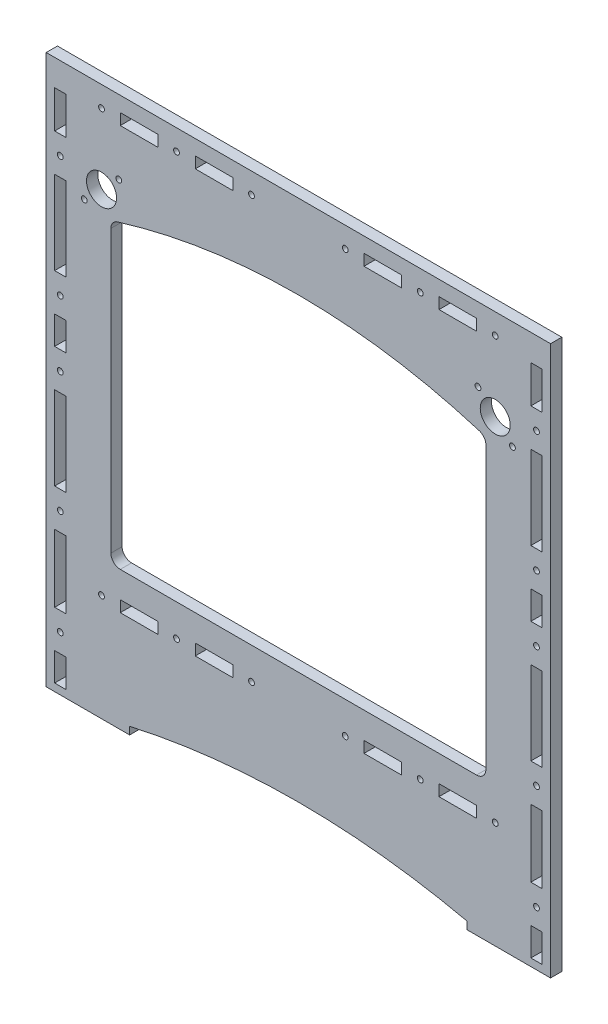
SolidWorks part; units mm, degrees
ref_plane "Front Plane" through (0, 0, 0) normal (0, 0, 1) x (1, 0, 0)
ref_plane "Top Plane" through (0, 0, 0) normal (0, 1, 0) x (1, 0, 0)
ref_plane "Right Plane" through (0, 0, 0) normal (1, 0, 0) x (0, 0, -1)
sketch "Sketch1" plane through (0, 0, 0) normal (0, 0, 1) x (1, 0, 0)
  line L1 (0, 0) -> (260, 0)
  line L2 (0, 0) -> (0, 270)
  line L3 (0, 270) -> (260, 270)
  line L4 (260, 0) -> (260, 270)
  dimension "D1" = 270
  dimension "D2" = 260
extrude "Boss-Extrude1" add sketch "Sketch1" along normal blind 6
sketch "Sketch2" plane through (0, 0, 0) normal (0, 0, -1) x (-1, 0, 0)
  line L0 (-130, 270) -> (-130, 0) construction
  line L1 (-225, 56) -> (-205, 56)
  line L2 (-225, 56) -> (-225, 50)
  line L3 (-225, 50) -> (-205, 50)
  line L4 (-205, 56) -> (-205, 50)
  line L5 (-185, 56) -> (-165, 56)
  line L6 (-185, 56) -> (-185, 50)
  line L7 (-185, 50) -> (-165, 50)
  line L8 (-165, 56) -> (-165, 50)
  line L9 (-260, 270) -> (0, 270) construction
  line L10 (0, 0) -> (-260, 0) construction
  line L11 (-260, 0) -> (-260, 270) construction
  line L12 (-225, 53) -> (-165, 53) construction
  line L13 (-130, 0) -> (-130, -73.8705) construction
  line L14 (-130, -73.8705) -> (-130, -196.098) construction
  line L16 (-220, 0) -> (-40, 0)
  line L17 (-75, 50) -> (-95, 50)
  line L18 (-95, 56) -> (-95, 50)
  line L19 (-75, 56) -> (-95, 56)
  line L20 (-75, 56) -> (-75, 50)
  line L21 (-35, 50) -> (-55, 50)
  line L22 (-55, 56) -> (-55, 50)
  line L23 (-35, 56) -> (-55, 56)
  line L24 (-35, 56) -> (-35, 50)
  arc A0 (-220, 0) -> (-40, 0) centre (-130, -400) cw
  point P23 (-130, 10)
  point P26 (-130, 10)
  dimension "D9" = 40
  dimension "D1" = 35
  dimension "D2" = 20
  dimension "D3" = 20
  dimension "D4" = 20
  dimension "D5" = 6
  dimension "D6" = 6
  dimension "D7" = 50
  dimension "D8" = 3
  dimension "D12" = 10
extrude "Cut-Extrude1" cut sketch "Sketch2" against normal blind 6
sketch "Sketch3" plane through (0, 0, 0) normal (0, 0, -1) x (-1, 0, 0)
  line L0 (-260, 0) -> (-260, 270) construction
  line L1 (-225, 70) -> (-35, 70)
  line L2 (-230, 75) -> (-230, 220)
  line L4 (-30, 75) -> (-30, 220)
  line L5 (0, 270) -> (0, 0) construction
  line L6 (-220, 0) -> (-260, 0) construction
  line L7 (-260, 270) -> (0, 270) construction
  line L16 (-35, 225) -> (-225, 225)
  arc A0 (-35, 70) -> (-30, 75) centre (-35, 75) ccw
  arc A1 (-225, 70) -> (-230, 75) centre (-225, 75) cw
  arc A2 (-230, 220) -> (-225, 225) centre (-225, 220) cw
  arc A3 (-35, 225) -> (-30, 220) centre (-35, 220) cw
  dimension "D5" = 5
  dimension "D6" = 45
  dimension "D4" = 5
  dimension "D1" = 30
  dimension "D2" = 30
  dimension "D3" = 70
extrude "Cut-Extrude2" cut sketch "Sketch3" against normal blind 10 contours L4 A3 L16 A2 L2 A1 L1 A0
sketch "Sketch4" plane through (0, 0, 0) normal (0, 0, -1) x (-1, 0, 0)
  line L1 (-260, 270) -> (-254, 270)
  line L2 (-260, 270) -> (-260, 264)
  line L5 (-220, 0) -> (-260, 0) construction
  line L6 (-260, 270) -> (-254, 270)
  line L7 (-260, 270) -> (-260, 255)
  line L8 (-260, 0) -> (-254, 0)
  line L9 (-254, 264) -> (-254, 255)
  line L11 (-254, 15) -> (-260, 15)
  line L13 (-254, 35) -> (-260, 35)
  line L15 (-254, 71) -> (-260, 71)
  line L17 (-254, 91) -> (-260, 91)
  line L19 (-260, 135.5) -> (-254, 135.5)
  line L21 (-260, 155.5) -> (-254, 155.5)
  line L23 (-254, 170.5) -> (-260, 170.5)
  line L25 (-254, 190.5) -> (-260, 190.5)
  line L27 (-254, 235) -> (-260, 235)
  line L29 (-254, 255) -> (-260, 255)
  line L33 (-254, 264) -> (-254, 270)
  line L36 (-205, 56) -> (-225, 56) construction
  line L38 (-130, 270) -> (-130, 0) construction
  line L39 (-260, 270) -> (0, 270) construction
  line L40 (-260, 15) -> (-260, 0)
  line L41 (-260, 270) -> (-254, 270)
  line L42 (-260, 270) -> (-260, 255)
  line L43 (-260, 255) -> (-254, 255)
  line L44 (-254, 270) -> (-254, 255)
  line L45 (-260, 235) -> (-254, 235)
  line L46 (-260, 235) -> (-260, 190.5)
  line L47 (-260, 190.5) -> (-254, 190.5)
  line L48 (-254, 235) -> (-254, 190.5)
  line L49 (-260, 170.5) -> (-254, 170.5)
  line L50 (-260, 170.5) -> (-260, 155.5)
  line L51 (-260, 155.5) -> (-254, 155.5)
  line L52 (-254, 170.5) -> (-254, 155.5)
  line L53 (-260, 135.5) -> (-254, 135.5)
  line L54 (-260, 135.5) -> (-260, 91)
  line L55 (-260, 91) -> (-254, 91)
  line L56 (-254, 135.5) -> (-254, 91)
  line L57 (-260, 71) -> (-254, 71)
  line L58 (-260, 71) -> (-260, 35)
  line L59 (-260, 35) -> (-254, 35)
  line L60 (-254, 71) -> (-254, 35)
  line L61 (-260, 15) -> (-254, 15)
  line L62 (-260, 15) -> (-260, 0)
  line L63 (-260, 0) -> (-254, 0)
  line L64 (-254, 15) -> (-254, 0)
  line L65 (-254, 71) -> (-254, 35)
  line L66 (-260, 71) -> (-260, 35)
  line L67 (-254, 135.5) -> (-254, 91)
  line L68 (-260, 135.5) -> (-260, 91)
  line L69 (-254, 170.5) -> (-254, 155.5)
  line L70 (-260, 170.5) -> (-260, 155.5)
  line L71 (-254, 235) -> (-254, 190.5)
  line L72 (-260, 235) -> (-260, 190.5)
  line L73 (-254, 15) -> (-254, 0)
  line L74 (0, 0) -> (-6, 0)
  line L75 (-6, 15) -> (-6, 0)
  line L76 (0, 15) -> (-6, 15)
  line L77 (0, 15) -> (0, 0)
  line L78 (0, 35) -> (-6, 35)
  line L79 (-6, 71) -> (-6, 35)
  line L80 (0, 71) -> (-6, 71)
  line L81 (0, 71) -> (0, 35)
  line L82 (0, 91) -> (-6, 91)
  line L83 (-6, 135.5) -> (-6, 91)
  line L84 (0, 135.5) -> (-6, 135.5)
  line L85 (0, 135.5) -> (0, 91)
  line L86 (0, 155.5) -> (-6, 155.5)
  line L87 (-6, 170.5) -> (-6, 155.5)
  line L88 (0, 170.5) -> (-6, 170.5)
  line L89 (0, 170.5) -> (0, 155.5)
  line L90 (0, 190.5) -> (-6, 190.5)
  line L91 (-6, 235) -> (-6, 190.5)
  line L92 (0, 235) -> (-6, 235)
  line L93 (0, 235) -> (0, 190.5)
  line L94 (0, 255) -> (-6, 255)
  line L95 (-6, 270) -> (-6, 255)
  line L96 (0, 270) -> (-6, 270)
  line L97 (0, 270) -> (0, 255)
  point P33 (-257, 170.5)
  point P34 (-257, 71)
  line M60 (-40, 0) -> (0, 0)
  line M61 (0, 0) -> (0, 270)
  line M62 (0, 270) -> (-260, 270)
  line M63 (-260, 270) -> (-260, 0)
  line M64 (-260, 0) -> (-220, 0)
  dimension "D1" = 6
  dimension "D2" = 15
  dimension "D3" = 20
  dimension "D4" = 20
  dimension "D5" = 15
  dimension "D6" = 44.5
  dimension "D7" = 15
  dimension "D8" = 20
  dimension "D10" = 20
  dimension "D11" = 20
  dimension "D12" = 15
extrude "Cut-Extrude3" cut sketch "Sketch4" against normal blind 6 contours L9 L33 L29 M62 M63 | L48 L27 L25 M63 | L52 L23 L21 M63 | L56 L19 L17 M63 | L60 L15 L13 M63 | L64 L11 M63 M64 | L76 L75 M61 M60 | L80 L79 L78 M61 | L84 L83 L82 M61 | L92 L91 L90 M61 | L95 L94 M62 M61 | L89 L86 L87 L88
sketch "Sketch5" plane through (0, 0, 0) normal (0, 0, -1) x (-1, 0, 0)
  line L0 (-254, 270) -> (-6, 270) construction
  line L1 (-260, 235) -> (-260, 255) construction
  line L2 (-130, 270) -> (-130, 216.3233) construction
  circle A0 centre (-235, 240.5) radius 8
  circle A1 centre (-25, 240.5) radius 8
  dimension "D1" = 16
  dimension "D3" = 25
  dimension "D2" = 29.5
extrude "Cut-Extrude4" cut sketch "Sketch5" against normal blind 10
sketch "Sketch6" plane through (0, 0, 6) normal (0, 0, 1) x (1, 0, 0)
  line L0 (130, 270) -> (130, 181.7684) construction
  line L1 (254, 270) -> (6, 270) construction
  line L2 (17, 240.5) -> (33, 240.5) construction
  line L3 (25, 238) -> (25, 222) construction
  line L4 (15.8165, 231.2987) -> (34.2013, 249.6835) construction
  circle A0 centre (25, 240.5) radius 8 construction
  circle A2 centre (34.2013, 249.6835) radius 1.55
  circle A3 centre (15.8165, 231.2987) radius 1.55
  circle A4 centre (225.7987, 249.6835) radius 1.55
  circle A5 centre (244.1835, 231.2987) radius 1.55
  dimension "D4" = 3.1
  dimension "D5" = 9.1835
  dimension "D6" = 3.1
  dimension "D1" = 45
  dimension "D2" = 13
  dimension "D3" = 13
extrude "Cut-Extrude5" cut sketch "Sketch6" against normal blind 6
sketch "Sketch7" plane through (0, 0, 6) normal (0, 0, 1) x (1, 0, 0)
  line L0 (130, 270) -> (130, -437.6573) construction
  line L1 (254, 270) -> (6, 270) construction
  line L2 (230, 75) -> (230, 220) construction
  line L9 (225, 70) -> (35, 70) construction
  line L10 (30, 225) -> (30, 202.9048)
  line L11 (30, 75) -> (30, 220) construction
  line L12 (30, 202.9048) -> (230, 202.9048)
  line L13 (230, 202.9048) -> (230, 225)
  arc A0 (33.5299, 229.779) -> (226.4701, 229.779) centre (130, -83.8287) cw
  arc A1 (226.4701, 229.779) -> (230, 225) centre (225, 225) cw
  arc A2 (33.5299, 229.779) -> (30, 225) centre (35, 225) ccw
  point P16 (230, 220)
  point P19 (30, 220)
  dimension "D1" = 328.1101
  dimension "D2" = 5
  dimension "D3" = 155
extrude "Cut-Extrude7" cut sketch "Sketch7" against normal blind 10 contours L13 A1 A0 A2 L10 L12
sketch "Sketch8" plane through (0, 270, 0) normal (0, 1, 0) x (1, 0, 0)
  line L4 (254, 0) -> (6, 0)
  line L5 (6, 0) -> (6, -6)
  line L6 (6, -6) -> (254, -6)
  line L7 (254, -6) -> (254, 0)
  line L8 (254, 0) -> (6, 0)
  line L9 (6, 0) -> (6, -6)
  line L10 (6, -6) -> (254, -6)
  line L11 (254, -6) -> (254, 0)
  dimension "D1" = 0
extrude "Boss-Extrude2" add sketch "Sketch8" along normal blind 5
sketch "Sketch9" plane through (0, 0, 6) normal (0, 0, 1) x (1, 0, 0)
  line L0 (0, 255) -> (0, 235) construction
  line L1 (0, 275) -> (-4.5, 275)
  line L2 (0, 270) -> (0, 0)
  line L3 (0, 0) -> (-4.5, 0)
  line L4 (-4.5, 275) -> (-4.5, 0)
  line L5 (6, 275) -> (6, 255) construction
  line L6 (-4.5, 275) -> (6, 275)
  line L7 (-4.5, 275) -> (-4.5, 270)
  line L8 (0, 270) -> (6, 270)
  line L9 (6, 275) -> (6, 270)
  line L10 (130, 275) -> (130, 300) construction
  line L11 (6, 275) -> (254, 275) construction
  line L12 (264.5, 275) -> (264.5, 0)
  line L13 (260, 0) -> (264.5, 0)
  line L14 (260, 270) -> (260, 0)
  line L15 (254, 275) -> (254, 270)
  line L16 (260, 270) -> (254, 270)
  line L17 (264.5, 275) -> (264.5, 270)
  line L18 (264.5, 275) -> (254, 275)
  line L19 (260, 275) -> (264.5, 275)
  dimension "D1" = 4.5
  dimension "D2" = 0
  dimension "D3" = 5
extrude "Boss-Extrude3" add sketch "Sketch9" against normal blind 6 contours L6 L9 L8 L2 L3 L4 | L12 L13 L14 L16 L15 L18
sketch "Sketch10" plane through (0, 0, 6) normal (0, 0, 1) x (1, 0, 0)
  line L0 (-4.5, 275) -> (264.5, 275) construction
  line L1 (6, 270) -> (0, 270)
  line L2 (6, 270) -> (6, 275)
  line L3 (6, 275) -> (0, 275)
  line L4 (0, 270) -> (0, 275)
  line L5 (260, 270) -> (260, 255) construction
  line L6 (254, 270) -> (260, 270)
  line L7 (254, 270) -> (254, 275)
  line L8 (254, 275) -> (260, 275)
  line L9 (260, 270) -> (260, 275)
  dimension "D1" = 0
extrude "Cut-Extrude8" cut sketch "Sketch10" against normal blind 6
sketch "Sketch11" plane through (0, 0, 6) normal (0, 0, 1) x (1, 0, 0)
  line L0 (130, 275) -> (130, 242.0916) construction
  line L1 (6, 275) -> (254, 275) construction
  line L2 (0, 255) -> (6, 255) construction
  line L3 (6, 275) -> (6, 255) construction
  line L4 (0, 190.5) -> (6, 190.5) construction
  line L5 (0, 155.5) -> (6, 155.5) construction
  line L6 (0, 135.5) -> (0, 91) construction
  line L7 (0, 170.5) -> (0, 155.5) construction
  line L8 (0, 91) -> (6, 91) construction
  line L9 (0, 35) -> (6, 35) construction
  line L10 (0, 71) -> (0, 35) construction
  circle A0 centre (3, 245) radius 1.55
  circle A1 centre (3, 180.5) radius 1.55
  circle A2 centre (3, 145.5) radius 1.55
  circle A3 centre (3, 81) radius 1.55
  circle A4 centre (3, 25) radius 1.55
  circle A5 centre (257, 25) radius 1.55
  circle A6 centre (257, 81) radius 1.55
  circle A7 centre (257, 145.5) radius 1.55
  circle A8 centre (257, 180.5) radius 1.55
  circle A9 centre (257, 245) radius 1.55
  dimension "D1" = 3.1
  dimension "D4" = 3.1
  dimension "D5" = 3.1
  dimension "D6" = 10
  dimension "D7" = 10
  dimension "D8" = 3
  dimension "D9" = 3
  dimension "D10" = 3.1
  dimension "D11" = 10
  dimension "D12" = 3
  dimension "D13" = 3.1
  dimension "D14" = 10
  dimension "D15" = 3
  dimension "D2" = 10
  dimension "D3" = 3
extrude "Cut-Extrude9" cut sketch "Sketch11" against normal blind 6
sketch "Sketch12" plane through (0, 0, 6) normal (0, 0, 1) x (1, 0, 0)
  line L0 (-4.5, 53) -> (264.5, 53) construction
  line L3 (-4.5, 275) -> (-4.5, 0) construction
  line L4 (264.5, 275) -> (264.5, 0) construction
  line L6 (35, 50) -> (35, 56) construction
  line L7 (55, 50) -> (35, 50) construction
  line L8 (55, 56) -> (55, 50) construction
  line L10 (130, 53) -> (130, 63.8014) construction
  line L11 (95, 56) -> (95, 50) construction
  circle A0 centre (25, 53) radius 1.55
  circle A1 centre (65, 53) radius 1.55
  circle A3 centre (155, 53) radius 1.55
  circle A4 centre (155, 53) radius 1.55
  circle A5 centre (195, 53) radius 1.55
  circle A6 centre (235, 53) radius 1.55
  circle A7 centre (105, 53) radius 1.55
  point P7 (-4.5, 53)
  dimension "D1" = 3.1
  dimension "D3" = 3
  dimension "D4" = 3.1
  dimension "D5" = 10
  dimension "D6" = 3.1
  dimension "D7" = 3.1
  dimension "D8" = 50
  dimension "D9" = 10
  dimension "D2" = 10
extrude "Cut-Extrude10" cut sketch "Sketch12" against normal blind 10 contours A0 | A1 | A7 | A5 | A6 | A3
sketch "Sketch13" plane through (0, 275, 0) normal (0, 1, 0) x (1, 0, 0)
  line L1 (-4.5, -6) -> (264.5, -6)
  line L2 (-4.5, -6) -> (-4.5, 0)
  line L3 (-4.5, 0) -> (264.5, 0)
  line L4 (264.5, -6) -> (264.5, 0)
extrude "Boss-Extrude4" add sketch "Sketch13" along normal blind 14
sketch "Sketch14" plane through (0, 0, 0) normal (0, -1, 0) x (1, 0, 0)
  line L0 (40, 4.8099) -> (40, 0)
  line L1 (-4.5, 0) -> (40, 0)
  line L2 (-4.5, 0) -> (-4.5, 6)
  line L3 (220, 6) -> (264.5, 6)
  line L4 (264.5, 0) -> (264.5, 6)
  line L5 (40, 6) -> (40, 0) construction
  line L7 (220, 6) -> (220, 0)
  line L8 (220, 0) -> (264.5, 0)
  line L9 (40, 0) -> (-4.5, 0)
  line L10 (40, 0) -> (40, 6)
  line L11 (40, 6) -> (-4.5, 6)
  line L12 (-4.5, 0) -> (-4.5, 6)
  line M1 (40, 6) -> (6, 6)
  line M2 (6, 6) -> (6, 0)
  line M3 (6, 0) -> (40, 0)
  line M4 (40, 0) -> (40, 6)
extrude "Boss-Extrude5" add sketch "Sketch14" along normal blind 4 contours M4 M1 M2 M3 | L11 L2 L1 M2 | L7 L8 L4 L3
sketch "Sketch15" plane through (0, 0, 6) normal (0, 0, 1) x (1, 0, 0)
  line L13 (55, 275) -> (35, 275)
  line L40 (35, 275) -> (35, 281)
  line L41 (35, 281) -> (55, 281)
  line L42 (55, 281) -> (55, 275)
  line L43 (95, 281) -> (95, 275)
  line L44 (95, 275) -> (75, 275)
  line L45 (75, 275) -> (75, 281)
  line L46 (75, 281) -> (95, 281)
  line L55 (-4.5, 289) -> (264.5, 289) construction
  line L57 (130, 289) -> (130, 336.332) construction
  line L58 (185, 281) -> (165, 281)
  line L59 (185, 275) -> (185, 281)
  line L60 (165, 275) -> (185, 275)
  line L61 (165, 281) -> (165, 275)
  line L62 (205, 281) -> (205, 275)
  line L63 (225, 281) -> (205, 281)
  line L64 (225, 275) -> (225, 281)
  line L65 (205, 275) -> (225, 275)
  circle A1 centre (25, 278) radius 1.55
  circle A14 centre (105, 278) radius 1.55
  circle A15 centre (65, 278) radius 1.55
  circle A19 centre (195, 278) radius 1.55
  circle A20 centre (155, 278) radius 1.55
  circle A21 centre (235, 278) radius 1.55
  point P10 (130, 289)
  dimension "D3" = 11
  dimension "D1" = 11
  dimension "D2" = 10
  dimension "D4" = 11
  dimension "D5" = 25
  dimension "D6" = 40
extrude "Cut-Extrude11" cut sketch "Sketch15" against normal blind 10
